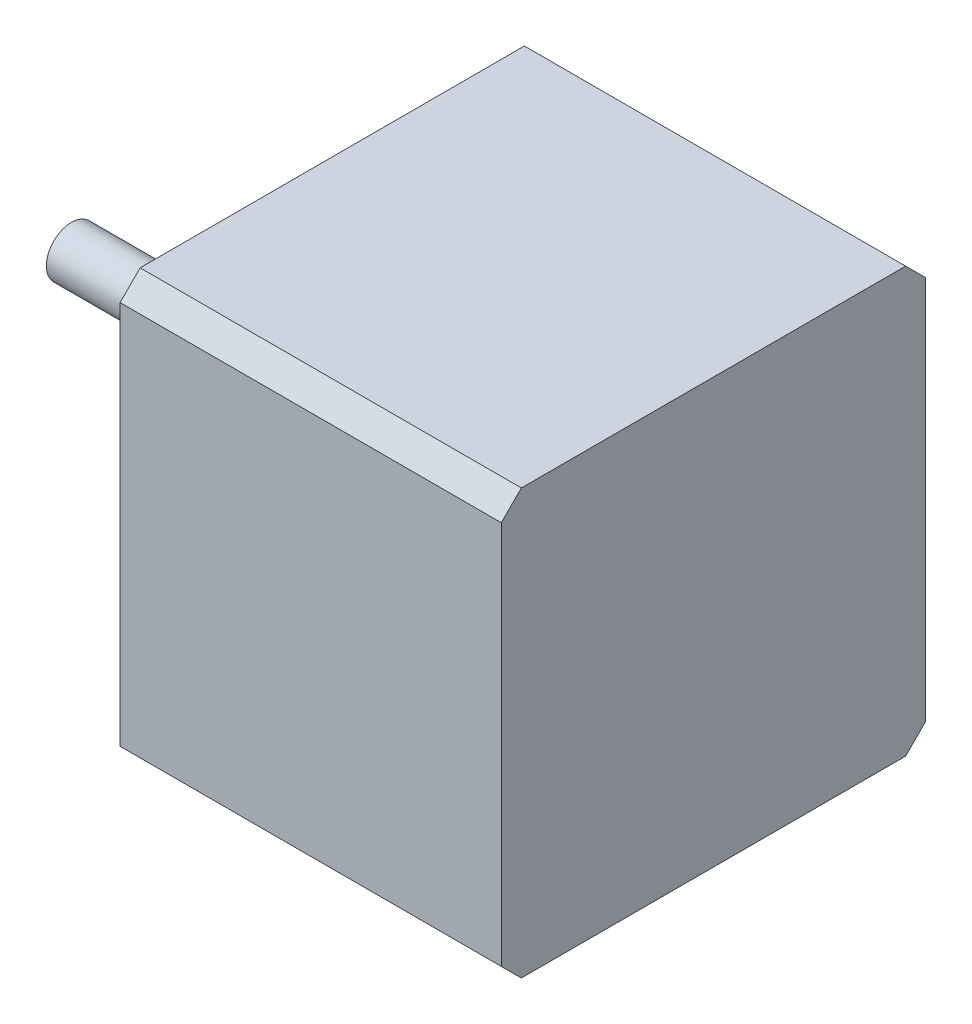
SolidWorks part; units mm, degrees
ref_plane "前视基准面" through (0, 0, 0) normal (0, 0, 1) x (1, 0, 0)
ref_plane "上视基准面" through (0, 0, 0) normal (0, 1, 0) x (1, 0, 0)
ref_plane "右视基准面" through (0, 0, 0) normal (1, 0, 0) x (0, 0, -1)
sketch "草图1" plane through (0, 0, 0) normal (1, 0, 0) x (0, 0, -1)
  line L0 (0, 40.3) -> (2, 42.3)
  line L1 (2, 0) -> (40.3, 0)
  line L2 (0, 2) -> (0, 40.3)
  line L3 (2, 42.3) -> (40.3, 42.3)
  line L4 (42.3, 2) -> (42.3, 40.3)
  line L5 (40.3, 42.3) -> (42.3, 40.3)
  line L6 (0, 2) -> (2, 0)
  line L7 (40.3, 0) -> (42.3, 2)
  point P0 (0, 0)
  point P1 (42.3, 42.3)
  point P2 (0, 42.3)
  point P3 (42.3, 0)
extrude "凸台-拉伸2" add sketch "草图1" along normal blind 38 contours L3 L5 L4 L7 L1 L6 L2 L0
sketch "草图2" plane through (0, 0, 0) normal (-1, 0, 0) x (0, 0, 1)
  circle A0 centre (-21.15, 21.15) radius 11
extrude "凸台-拉伸3" add sketch "草图2" along normal blind 2
fillet "圆角1" radius 1 1 edges at (-2, 21.15, -10.15)
sketch "草图3" plane through (-2, 0, 0) normal (-1, 0, 0) x (0, 0, 1)
  circle A0 centre (-21.15, 21.15) radius 2.5
extrude "凸台-拉伸4" add sketch "草图3" along normal blind 24 contours A0
sketch "草图4" plane through (0, 0, 0) normal (-1, 0, 0) x (0, 0, 1)
  circle A0 centre (-36.65, 36.65) radius 1.5
extrude "切除-拉伸1" cut sketch "草图4" against normal blind 4.5
pattern_circular "阵列(圆周)1" count 4 over 360 about axis through (0, 21.15, -21.15) along (1, 0, 0) of "切除-拉伸1"
